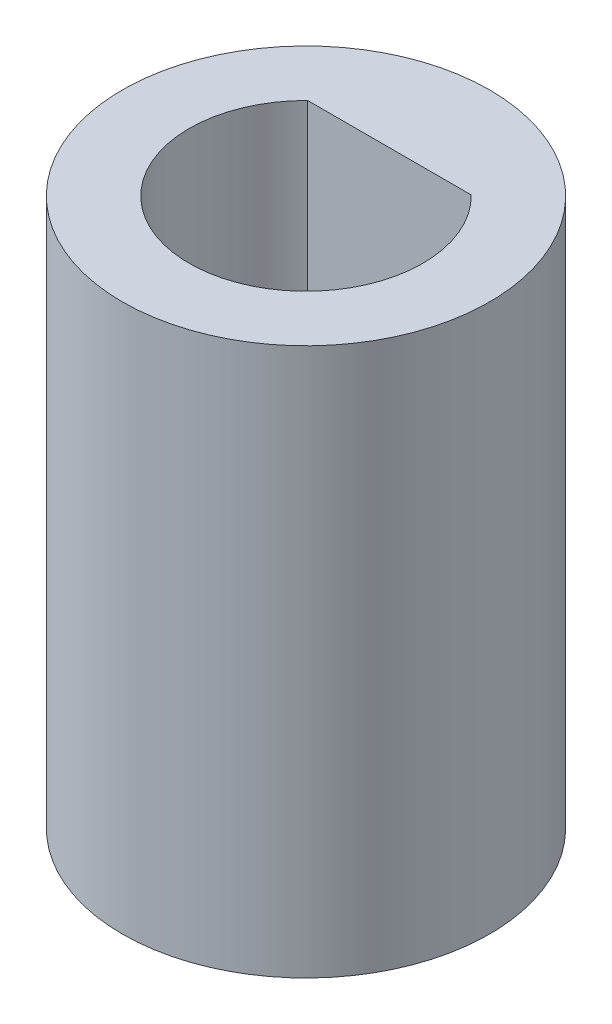
SolidWorks part; units mm, degrees
ref_plane "Front Plane" through (0, 0, 0) normal (0, 0, 1) x (1, 0, 0)
ref_plane "Top Plane" through (0, 0, 0) normal (0, 1, 0) x (1, 0, 0)
ref_plane "Right Plane" through (0, 0, 0) normal (1, 0, 0) x (0, 0, -1)
sketch "Sketch1" plane through (0, 0, 0) normal (0, 1, 0) x (1, 0, 0)
  line L0 (-2.4495, 2.5) -> (2.4495, 2.5) construction
  circle A0 centre (0, 0) radius 5.5
  circle A1 centre (0, 0) radius 3.5 construction
  arc A2 (-2.4495, 2.5) -> (2.4495, 2.5) centre (0, 0) ccw construction
  point P6 (0, -3.5)
  dimension "D1" = 7
  dimension "D2" = 2
  dimension "D3" = 6
extrude "Boss-Extrude1" add sketch "Sketch1" against normal blind 16.4
ref_plane "Plane1" through (0, 0, 0) normal (0, 1, 0) x (1, 0, 0)
sketch "Sketch3" plane through (0, 0, 0) normal (0, 1, 0) x (1, 0, 0)
  line L0 (-2.4495, 2.5) -> (2.4495, 2.5) construction
  line L1 (-2.4495, 2.5) -> (2.4495, 2.5)
  circle A0 centre (0, 0) radius 3.5 construction
  arc A1 (-2.4495, 2.5) -> (2.4495, 2.5) centre (0, 0) ccw
extrude "Cut-Extrude1" cut sketch "Sketch3" against normal through all
